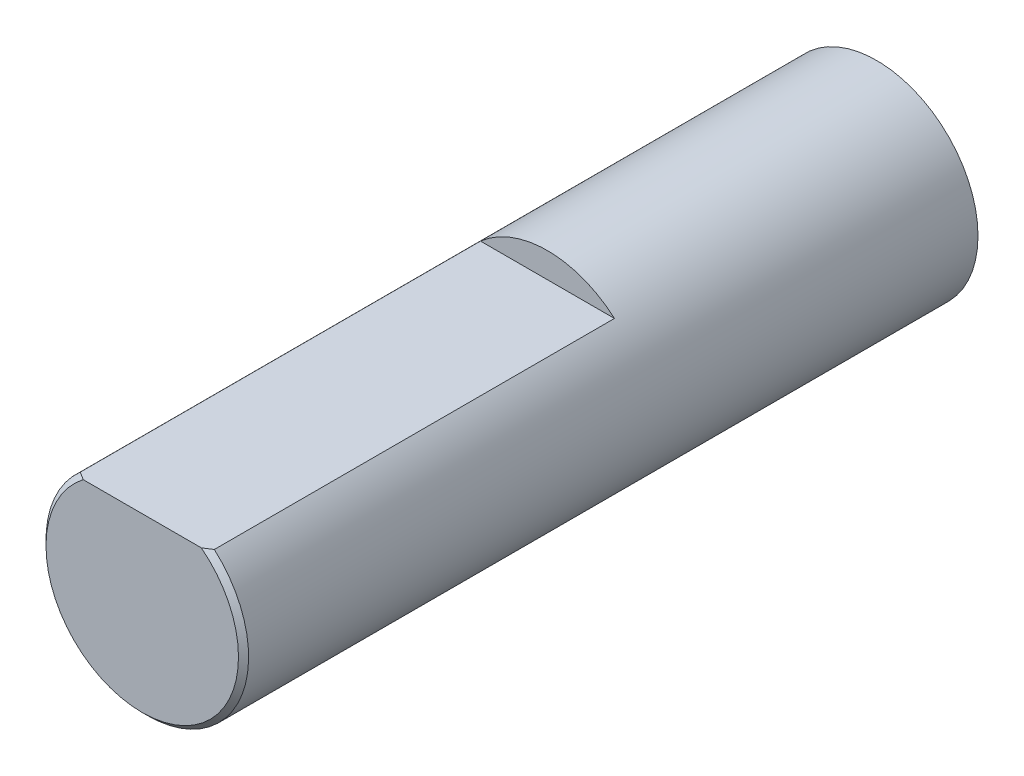
SolidWorks part; units mm, degrees
material "Cast Alloy Steel"
ref_plane "Front Plane" through (0, 0, 0) normal (0, 0, 1) x (1, 0, 0)
ref_plane "Top Plane" through (0, 0, 0) normal (0, 1, 0) x (1, 0, 0)
ref_plane "Right Plane" through (0, 0, 0) normal (1, 0, 0) x (0, 0, -1)
sketch "Sketch1" plane through (0, 0, 0) normal (0, 0, 1) x (1, 0, 0)
  circle A0 centre (0, 0) radius 2
  dimension "D1" = 4
extrude "Boss-Extrude1" add sketch "Sketch1" along normal blind 14.5
sketch "Sketch2" plane through (0, 0, 14.5) normal (0, 0, 1) x (1, 0, 0)
  line L0 (-1.3229, 1.5) -> (1.3229, 1.5)
  circle A0 centre (0, 0) radius 2 construction
  arc A1 (1.3229, 1.5) -> (-1.3229, 1.5) centre (0, 0) ccw
  dimension "D1" = 1.5
extrude "Cut-Extrude1" cut sketch "Sketch2" against normal blind 8
chamfer "Chamfer1" distance 0.1 angle 45 1 edges at (0, -2, 14.5)
